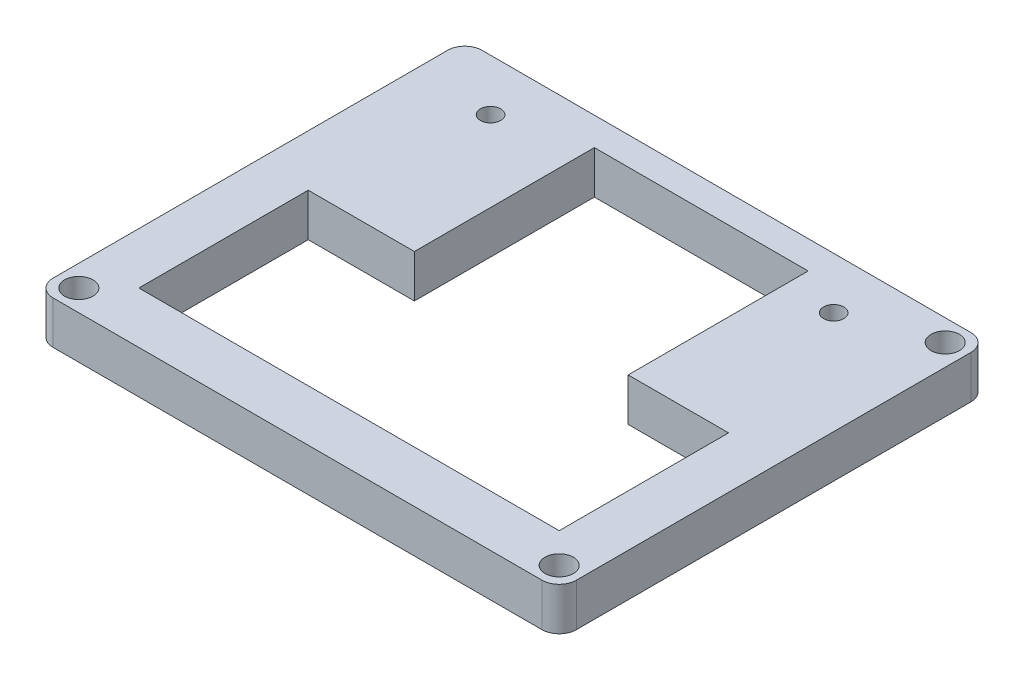
SolidWorks part; units mm, degrees
ref_plane "Front Plane" through (0, 0, 0) normal (0, 0, 1) x (1, 0, 0)
ref_plane "Top Plane" through (0, 0, 0) normal (0, 1, 0) x (1, 0, 0)
ref_plane "Right Plane" through (0, 0, 0) normal (1, 0, 0) x (0, 0, -1)
sketch "Sketch1" plane through (0, 0, 0) normal (0, 1, 0) x (1, 0, 0)
  line L1 (0, 0) -> (77.47, 0)
  line L2 (0, 0) -> (0, 63.5)
  line L3 (0, 63.5) -> (77.47, 63.5)
  line L4 (77.47, 0) -> (77.47, 63.5)
  line L5 (23.3376, 59.3441) -> (54.9824, 59.3441)
  line L6 (23.3376, 59.3441) -> (23.3376, 32.6975)
  line L7 (23.3376, 32.6975) -> (54.9824, 32.6975)
  line L8 (54.9824, 59.3441) -> (54.9824, 32.6975)
  line L9 (7.62, 32.6975) -> (69.85, 32.6975)
  line L10 (7.62, 32.6975) -> (7.62, 7.62)
  line L11 (7.62, 7.62) -> (69.85, 7.62)
  line L12 (69.85, 32.6975) -> (69.85, 7.62)
  dimension "D1" = 77.47
  dimension "D2" = 63.5
  dimension "D3" = 7.62
  dimension "D4" = 7.62
  dimension "D5" = 7.62
extrude "Boss-Extrude1" add sketch "Sketch1" along normal blind 6.35 contours L1 L4 L3 L2 L9 L12 L11 L10 L6 L5 L8
sketch "Sketch2" plane through (0, 6.35, 0) normal (0, 1, 0) x (1, 0, 0)
  line L0 (0, 63.5) -> (77.47, 63.5) construction
  line L1 (77.47, 0) -> (77.47, 63.5) construction
  line L2 (0, 0) -> (77.47, 0) construction
  line L3 (0, 0) -> (0, 63.5) construction
  circle A0 centre (3.175, 3.175) radius 2.1
  circle A1 centre (74.295, 3.175) radius 2.1
  circle A2 centre (74.295, 60.325) radius 2.1
  dimension "D1" = 4.2
  dimension "D2" = 3.175
  dimension "D3" = 3.175
  dimension "D4" = 3.175
  dimension "D5" = 3.175
extrude "Cut-Extrude1" cut sketch "Sketch2" against normal blind 6.35
fillet "Fillet1" radius 2.54 4 edges at (0, 3.175, -63.5) (77.47, 3.175, -63.5) (77.47, 3.175, 0) (0, 3.175, 0)
sketch "Sketch3" plane through (0, 6.35, 0) normal (0, 1, 0) x (1, 0, 0)
  line L0 (2.54, 63.5) -> (74.93, 63.5) construction
  line L2 (77.47, 2.54) -> (77.47, 60.96) construction
  circle A0 centre (11.43, 55.88) radius 1.5
  circle A1 centre (62.23, 55.88) radius 1.5
  point P8 (0, 0)
  point P9 (15.24, 55.88)
  point P10 (63.9008, 55.88)
  dimension "D4" = 3
  dimension "D1" = 7.62
  dimension "D2" = 15.24
  dimension "D3" = 50.8
extrude "Cut-Extrude2" cut sketch "Sketch3" against normal blind 10.16
